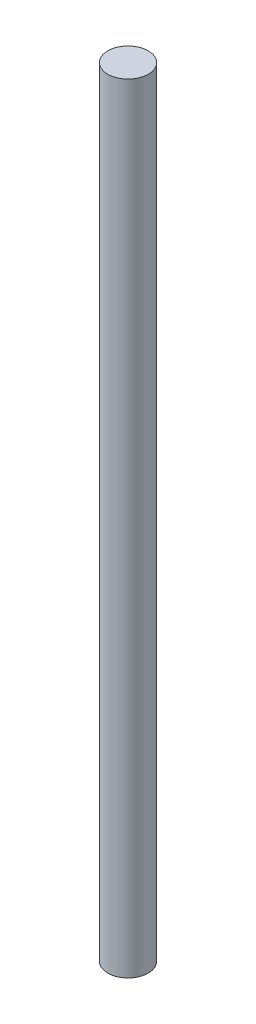
SolidWorks part; units mm, degrees
ref_plane "Front Plane" through (0, 0, 0) normal (0, 0, 1) x (1, 0, 0)
ref_plane "Top Plane" through (0, 0, 0) normal (0, 1, 0) x (1, 0, 0)
ref_plane "Right Plane" through (0, 0, 0) normal (1, 0, 0) x (0, 0, -1)
sketch "Sketch1" plane through (0, 0, 0) normal (0, 1, 0) x (1, 0, 0)
  circle A1 centre (0, 0) radius 3.9688
  dimension "D1" = 7.9375
extrude "Boss-Extrude1" add sketch "Sketch1" along normal blind 152.4
